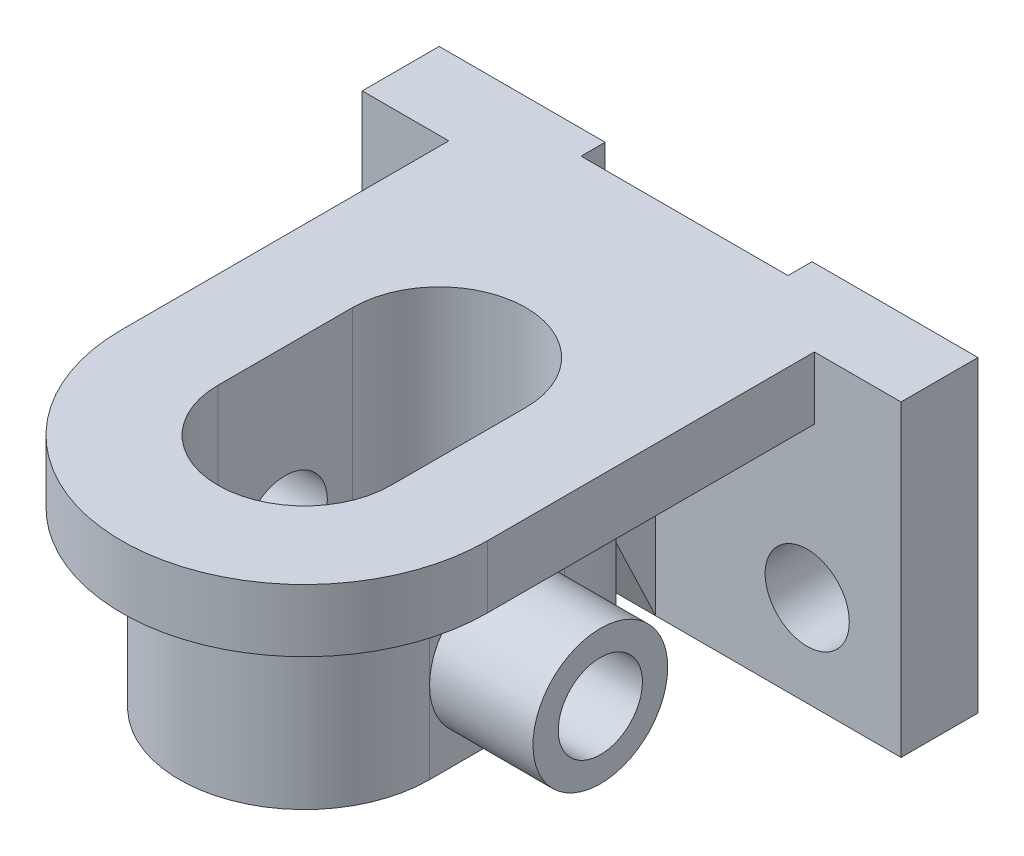
SolidWorks part; units mm, degrees
ref_plane "前视基准面" through (0, 0, 0) normal (0, 0, 1) x (1, 0, 0)
ref_plane "上视基准面" through (0, 0, 0) normal (0, 1, 0) x (1, 0, 0)
ref_plane "右视基准面" through (0, 0, 0) normal (1, 0, 0) x (0, 0, -1)
other "Configuration Table"
sketch "草图1" plane through (0, 0, 0) normal (0, 0, 1) x (1, 0, 0)
  line L0 (0, 76.7957) -> (0, -76.0772) construction
  line L1 (112, -64) -> (-112, -64)
  line L2 (112, -64) -> (112, 64)
  line L3 (112, 64) -> (-112, 64)
  line L4 (-112, -64) -> (-112, 64)
  line L5 (112, -64) -> (-112, 64) construction
  line L6 (112, 64) -> (-112, -64) construction
  circle A0 centre (73, -26) radius 17.5
  circle A1 centre (-73, -26) radius 17.5
  point P0 (0, 0)
  point P8 (0, -64)
  point P10 (0, 76.7957)
  point P12 (0, -76.0772)
  dimension "D3" = 73
  dimension "D5" = 35
  dimension "D1" = 224
  dimension "D2" = 128
  dimension "D4" = 90
extrude "凸台-拉伸1" add sketch "草图1" along normal blind 32
sketch "草图2" plane through (0, -64, 0) normal (0, -1, 0) x (1, 0, 0)
  line L1 (43, -10) -> (-43, -10)
  line L2 (43, -10) -> (43, 10)
  line L3 (43, 10) -> (-43, 10)
  line L4 (-43, -10) -> (-43, 10)
  line L5 (43, -10) -> (-43, 10) construction
  line L6 (43, 10) -> (-43, -10) construction
  point P0 (0, 0)
  dimension "D1" = 20
  dimension "D2" = 86
extrude "切除-拉伸1" cut sketch "草图2" against normal blind 145
sketch "草图3" plane through (0, 64, 0) normal (0, 1, 0) x (1, 0, 0)
  line L0 (112, -32) -> (-112, -32) construction
  line L2 (76, -168) -> (76, -32)
  line L3 (76, -32) -> (-76, -32)
  line L4 (-76, -168) -> (-76, -32)
  line L5 (76, -168) -> (-76, -32) construction
  line L6 (76, -32) -> (-76, -168) construction
  arc A0 (-76, -168) -> (76, -168) centre (0, -168) ccw
  point P0 (0, -100)
  dimension "D1" = 152
  dimension "D2" = 136
extrude "凸台-拉伸2" add sketch "草图3" against normal blind 26
sketch "草图4" plane through (0, 38, 0) normal (0, -1, 0) x (1, 0, 0)
  line L0 (-52, 168) -> (-52, 112)
  line L1 (52, 112) -> (52, 168)
  arc A0 (-52, 168) -> (52, 168) centre (0, 168) cw
  arc A1 (-52, 112) -> (52, 112) centre (0, 112) ccw
  dimension "D1" = 56
extrude "凸台-拉伸3" add sketch "草图4" along normal blind 72
sketch "草图5" plane through (0, -34, 0) normal (0, -1, 0) x (1, 0, 0)
  line L0 (-36, 168) -> (-36, 112)
  line L1 (36, 112) -> (36, 168)
  arc A0 (-36, 168) -> (36, 168) centre (0, 168) cw
  arc A1 (-36, 112) -> (36, 112) centre (0, 112) ccw
extrude "切除-拉伸2" cut sketch "草图5" against normal blind 131
sketch "草图6" plane through (-52, 0, 0) normal (-1, 0, 0) x (0, 0, 1)
  line L0 (32, 64) -> (168, 64) construction
  line L2 (0, 64) -> (0, -64) construction
  circle A0 centre (140, 0) radius 28
  point P2 (0, 0)
  point P4 (90.3629, 76.6081)
  dimension "D1" = 64
  dimension "D2" = 140
extrude "凸台-拉伸5" add sketch "草图6" along normal blind 43
sketch "草图7" plane through (52, 0, 0) normal (1, 0, 0) x (0, 0, -1)
  line L0 (-168, 64) -> (-32, 64) construction
  line L1 (0, -64) -> (0, 64) construction
  circle A0 centre (-140, 0) radius 28
  dimension "D1" = 64
  dimension "D2" = 140
extrude "凸台-拉伸6" add sketch "草图7" along normal blind 43
sketch "草图8" plane through (-95, 0, 0) normal (-1, 0, 0) x (0, 0, 1)
  circle A0 centre (140, 0) radius 17.5
extrude "切除-拉伸3" cut sketch "草图8" against normal blind 241
sketch "草图9" plane through (0, 0, 0) normal (1, 0, 0) x (0, 0, -1)
  line L2 (-52, -22) -> (-67.637, -22)
  line L4 (-52, -22) -> (-32, -64)
  line L6 (-67.637, -22) -> (-67.637, 38)
  line L7 (-112, 38) -> (-60, 38) construction
  line L8 (-67.637, 38) -> (-32, 38)
  line L9 (-32, 38) -> (-32, -64)
  dimension "D1" = 20
  dimension "D2" = 60
extrude "凸台-拉伸7" add sketch "草图9" along normal blind 10 and the other way blind 10
